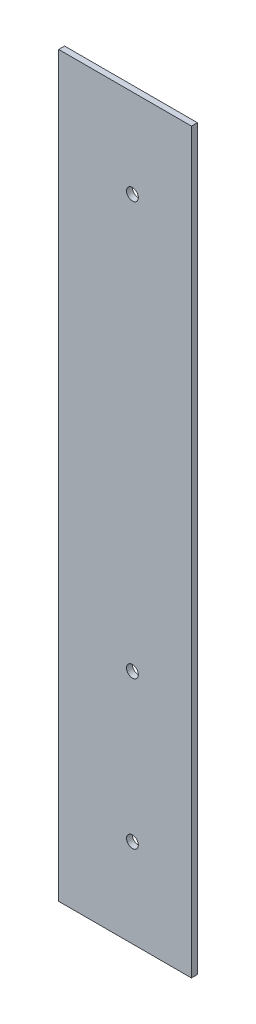
SolidWorks part; units mm, degrees
ref_plane "Front Plane" through (0, 0, 0) normal (0, 0, 1) x (1, 0, 0)
ref_plane "Top Plane" through (0, 0, 0) normal (0, 1, 0) x (1, 0, 0)
ref_plane "Right Plane" through (0, 0, 0) normal (1, 0, 0) x (0, 0, -1)
sketch "Sketch1" plane through (0, 0, 0) normal (0, 0, 1) x (1, 0, 0)
  line L1 (-22.5, 100) -> (22.5, 100)
  line L2 (-22.5, 100) -> (-22.5, -100)
  line L3 (-22.5, -100) -> (22.5, -100)
  line L4 (22.5, 100) -> (22.5, -100)
  line L5 (-22.5, 100) -> (22.5, -100) construction
  line L6 (-22.5, -100) -> (22.5, 100) construction
  point P0 (0, 0)
  dimension "D1" = 200
  dimension "D2" = 45
extrude "Boss-Extrude1" add sketch "Sketch1" along normal blind 2
sketch "Sketch2" plane through (0, 0, 2) normal (0, 0, 1) x (1, 0, 0)
  line L0 (-22.5, -100) -> (22.5, -100) construction
  line L1 (-22.5, 100) -> (-22.5, -100) construction
  line L2 (22.5, 100) -> (-22.5, 100) construction
  circle A1 centre (2.5, -70) radius 2
  circle A2 centre (2.5, 70) radius 2
  dimension "D1" = 4
  dimension "D2" = 4
  dimension "D3" = 30
  dimension "D4" = 25
  dimension "D5" = 30
  dimension "D6" = 25
extrude "Cut-Extrude1" cut sketch "Sketch2" against normal through all
sketch "Sketch3" plane through (0, 100, 0) normal (0, 1, 0) x (1, 0, 0)
  line L1 (-22.5, 0) -> (22.5, 0)
  line L2 (-22.5, 0) -> (-22.5, -2)
  line L3 (-22.5, -2) -> (22.5, -2)
  line L4 (22.5, 0) -> (22.5, -2)
sketch "Sketch5" plane through (0, -100, 0) normal (0, -1, 0) x (1, 0, 0)
  line L1 (-22.5, 2) -> (22.5, 2)
  line L2 (-22.5, 2) -> (-22.5, 0)
  line L3 (-22.5, 0) -> (22.5, 0)
  line L4 (22.5, 2) -> (22.5, 0)
extrude "Boss-Extrude3" add sketch "Sketch5" along normal blind 50
sketch "Sketch6" plane through (0, 0, 0) normal (0, 0, -1) x (-1, 0, 0)
  line L0 (22.5, 100) -> (22.5, -150) construction
  line L1 (22.5, -150) -> (-22.5, -150) construction
  circle A0 centre (-2.5, -120) radius 2
  dimension "D1" = 4
  dimension "D2" = 25
  dimension "D3" = 30
extrude "Cut-Extrude3" cut sketch "Sketch6" against normal blind 50
